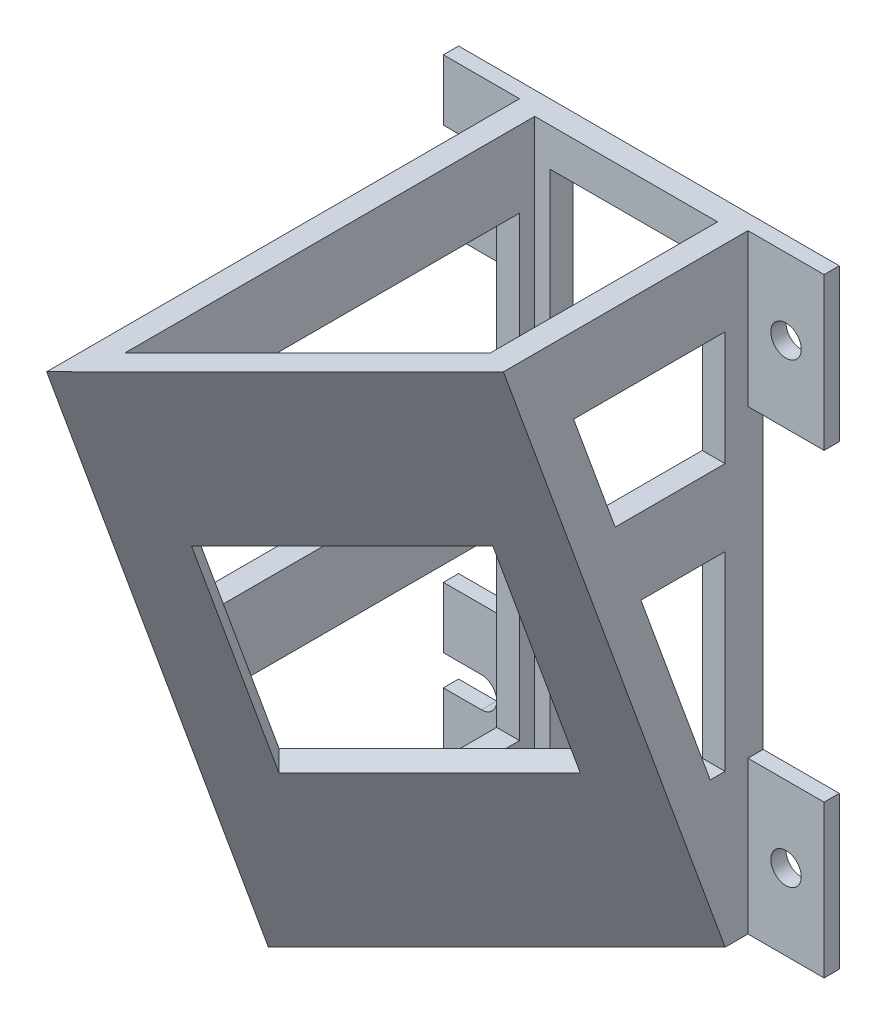
SolidWorks part; units mm, degrees
ref_plane "前视基准面" through (0, 0, 0) normal (0, 0, 1) x (1, 0, 0)
ref_plane "上视基准面" through (0, 0, 0) normal (0, 1, 0) x (1, 0, 0)
ref_plane "右视基准面" through (0, 0, 0) normal (1, 0, 0) x (0, 0, -1)
sketch "草图1" plane through (0, 0, 0) normal (0, 0, 1) x (1, 0, 0)
  line L1 (25, 40) -> (-25, 40)
  line L2 (25, 40) -> (25, -40)
  line L3 (25, -40) -> (-25, -40)
  line L4 (-25, 40) -> (-25, -40)
  line L5 (25, 40) -> (-25, -40) construction
  line L6 (25, -40) -> (-25, 40) construction
  point P0 (0, 0)
  dimension "D1" = 80
  dimension "D2" = 50
extrude "凸台-拉伸1" add sketch "草图1" along normal blind 80
sketch "草图4" plane through (0, 0, 80) normal (0, 0, 1) x (1, 0, 0)
  line L1 (-25, 40) -> (25, 40)
  line L2 (-25, 40) -> (-25, -120)
  line L3 (-25, -120) -> (25, -120)
  line L4 (25, 40) -> (25, -120)
  line L5 (-25, 40) -> (25, -120) construction
  line L6 (-25, -120) -> (25, 40) construction
  point P4 (0, -40)
  dimension "D1" = 160
revolve "切除-旋转2" cut sketch "草图4" angle 20 about L1
sketch "草图5" plane through (0, -21.0324, 57.786) normal (0, -0.342, 0.9397) x (1, 0, 0)
  line L1 (-25, 64.9493) -> (75, 64.9493)
  line L2 (-25, 64.9493) -> (-25, -95.0507)
  line L3 (-25, -95.0507) -> (75, -95.0507)
  line L4 (75, 64.9493) -> (75, -95.0507)
  line L5 (-25, 64.9493) -> (75, -95.0507) construction
  line L6 (-25, -95.0507) -> (75, 64.9493) construction
  point P4 (25, -15.0507)
  dimension "D1" = 100
  dimension "D2" = 160
revolve "切除-旋转4" cut sketch "草图5" angle 43.2 about L2
sketch "草图6" plane through (0, 0, 0) normal (0, 0, -1) x (-1, 0, 0)
  line L0 (25, -40) -> (-25, -40) construction
  line L1 (-15, -40) -> (-25, -40)
  line L2 (-15, -40) -> (-15, 40)
  line L3 (-15, 40) -> (-25, 40)
  line L4 (-25, -40) -> (-25, 40)
  line L5 (-15, -40) -> (-25, 40) construction
  line L6 (-15, 40) -> (-25, -40) construction
  line L7 (-25, 40) -> (25, 40) construction
  line L8 (-25, -40) -> (-25, 40) construction
  line L10 (25, -40) -> (14.9998, -40)
  line L11 (25, -40) -> (25, 40)
  line L12 (25, 40) -> (14.9998, 40)
  line L13 (14.9998, -40) -> (14.9998, 40)
  line L14 (25, -40) -> (14.9998, 40) construction
  line L15 (25, 40) -> (14.9998, -40) construction
  point P4 (-20, 0)
  point P15 (19.9999, 0)
  dimension "D1" = 10
  dimension "D2" = 0
extrude "切除-拉伸1" cut sketch "草图6" against normal blind 80
sketch "草图7" plane through (15, 0, 0) normal (1, 0, 0) x (0, 0, -1)
  line L0 (-40.0268, 40) -> (0, 40) construction
  line L1 (0, -40) -> (-5.91, -40)
  line L2 (0, -40) -> (0, 40)
  line L3 (0, 40) -> (-5.91, 40)
  line L4 (-5.91, -40) -> (-5.91, 40)
  line L5 (0, -40) -> (-5.91, 40) construction
  line L6 (0, 40) -> (-5.91, -40) construction
  point P4 (-2.955, 0)
  dimension "D1" = 5.91
extrude "切除-拉伸2" cut sketch "草图7" against normal blind 50
shell "抽壳2" thickness 3
sketch "草图8" plane through (0, 0, 5.91) normal (0, 0, -1) x (-1, 0, 0)
  line L0 (14.9998, -40) -> (-15, -40) construction
  line L1 (9.9998, -35) -> (-10, -35)
  line L2 (9.9998, -35) -> (9.9998, 35)
  line L3 (9.9998, 35) -> (-10, 35)
  line L4 (-10, -35) -> (-10, 35)
  line L5 (9.9998, -35) -> (-10, 35) construction
  line L6 (9.9998, 35) -> (-10, -35) construction
  line L7 (14.9998, 40) -> (-15, 40) construction
  line L8 (14.9998, 40) -> (14.9998, -40) construction
  line L9 (-15, 40) -> (-15, -40) construction
  point P4 (-0.0001, 0)
  dimension "D1" = 5
  dimension "D2" = 5
  dimension "D3" = 5
  dimension "D4" = 5
extrude "切除-拉伸3" cut sketch "草图8" against normal blind 3
sketch "草图9" plane through (0, 40, 0) normal (0, 1, 0) x (1, 0, 0)
  line L0 (12, -8.91) -> (-11.9998, -8.91)
  line L1 (-11.9998, -8.91) -> (-11.9998, -62.7673)
  line L2 (-11.9998, -62.7673) -> (12, -38.7836)
  line L3 (12, -38.7836) -> (12, -8.91)
  line L4 (-14.9998, -5.91) -> (15, -5.91) construction
  line L5 (15, -40.0268) -> (15, -5.91) construction
  line L6 (-14.9998, -70.0065) -> (-14.9998, -5.91) construction
  line L7 (15, -40.0268) -> (-14.9998, -70.0065) construction
  point P12 (0.0001, -50.7754)
  dimension "D1" = 3
  dimension "D2" = 3
  dimension "D3" = 3
  dimension "D4" = 0
  dimension "D5" = 3
extrude "切除-拉伸4" cut sketch "草图9" against normal blind 3
sketch "草图10" plane through (0, -40, 0) normal (0, -1, 0) x (1, 0, 0)
  line L0 (12.7565, 8.91) -> (-11.9998, 8.91)
  line L1 (-11.9998, 8.91) -> (-11.9998, 33.6496)
  line L2 (-11.9998, 33.6496) -> (12.7565, 8.91)
  line L3 (-14.9998, 5.91) -> (15, 5.91) construction
  line L4 (-14.9998, 40.8888) -> (-14.9998, 5.91) construction
  line L5 (-14.9998, 40.8888) -> (15, 10.9092) construction
  point P9 (0.3784, 21.2798)
  dimension "D1" = 3
  dimension "D2" = 3
  dimension "D3" = 0
  dimension "D4" = 3
extrude "切除-拉伸5" cut sketch "草图10" against normal blind 3
sketch "草图11" plane through (-14.9998, 0, 0) normal (-1, 0, 0) x (0, 0, 1)
  line L0 (10.91, -30) -> (10.91, -5)
  line L1 (10.91, -5) -> (48.3069, -5)
  line L2 (48.3069, -5) -> (39.2077, -30)
  line L3 (39.2077, -30) -> (10.91, -30)
  line L4 (10.91, 5) -> (10.91, 30)
  line L5 (10.91, 30) -> (61.0459, 30)
  line L6 (61.0459, 30) -> (51.9466, 5)
  line L7 (51.9466, 5) -> (10.91, 5)
  line L8 (40.8888, -40) -> (5.91, -40) construction
  line L9 (5.91, 40) -> (5.91, -40) construction
  line L10 (70.0065, 40) -> (5.91, 40) construction
  line L11 (40.8888, -40) -> (70.0065, 40) construction
  point P16 (43.7573, -17.5)
  point P17 (56.4962, 17.5)
  dimension "D1" = 10
  dimension "D2" = 5
  dimension "D3" = 10
  dimension "D4" = 360
  dimension "D5" = 0
  dimension "D6" = 5
  dimension "D7" = 5
  dimension "D8" = 10
  dimension "D9" = 25
  dimension "D10" = 25
extrude "切除-拉伸6" cut sketch "草图11" against normal blind 3
sketch "草图15" plane through (15, 0, 0) normal (1, 0, 0) x (0, 0, -1)
  line L0 (-30.8075, 30) -> (-10.91, 30)
  line L1 (-10.91, 30) -> (-10.91, 15)
  line L2 (-10.91, 15) -> (-25.348, 15)
  line L3 (-25.348, 15) -> (-30.8075, 30)
  line L4 (-40.0268, 40) -> (-5.91, 40) construction
  line L5 (-5.91, 40) -> (-5.91, -40) construction
  line L6 (-40.0268, 40) -> (-10.9092, -40) construction
  line L8 (-10.91, 5) -> (-10.91, -20)
  line L9 (-10.91, -20) -> (-12.8677, -20)
  line L10 (-12.8677, -20) -> (-21.967, 5)
  line L11 (-21.967, 5) -> (-10.91, 5)
  line L12 (-10.9092, -40) -> (-5.91, -40) construction
  point P16 (-17.4173, -7.5)
  dimension "D1" = 10
  dimension "D2" = 5
  dimension "D3" = 0
  dimension "D4" = 5
  dimension "D5" = 10
  dimension "D6" = 20
  dimension "D7" = 0
  dimension "D8" = 5
  dimension "D9" = 25
extrude "切除-拉伸7" cut sketch "草图15" against normal blind 3
sketch "草图17" plane through (18.9715, -6.9097, 18.9842) normal (0.6845, -0.2493, 0.685) x (0.729, 0.2341, -0.6433)
  line L0 (-39.6018, 0.4173) -> (-12.4481, -6.3482)
  line L1 (-12.4481, -6.3482) -> (-12.4481, 27.2575)
  line L2 (-12.4481, 27.2575) -> (-39.6018, 34.0229)
  line L3 (-39.6018, 34.0229) -> (-39.6018, 0.4173)
  line L4 (-5.4481, 51.2777) -> (-46.6018, 61.5313) construction
  line L5 (-5.4481, 51.2777) -> (-5.4481, -33.8565) construction
  line L6 (-46.6018, -23.6029) -> (-46.6018, 61.5313) construction
  line L7 (-46.6018, -23.6029) -> (-5.4481, -33.8565) construction
  point P12 (-12.4481, 10.4547)
  point P13 (-26.025, 30.6402)
  point P14 (-39.6018, 17.2201)
  point P15 (-26.025, -2.9654)
  point P17 (-21.9806, 24.8721)
  dimension "D1" = 0
  dimension "D2" = 0
  dimension "D3" = 0
  dimension "D4" = 0
  dimension "D5" = 7
  dimension "D6" = 25
  dimension "D7" = 7
  dimension "D8" = 25
extrude "切除-拉伸9" cut sketch "草图17" against normal blind 3
sketch "草图18" plane through (15, 0, 0) normal (1, 0, 0) x (0, 0, -1)
  line L1 (-5.91, -40) -> (-7.91, -40)
  line L2 (-5.91, -40) -> (-5.91, -20)
  line L3 (-5.91, -20) -> (-7.91, -20)
  line L4 (-7.91, -40) -> (-7.91, -20)
  line L5 (-5.91, -40) -> (-7.91, -20) construction
  line L6 (-5.91, -20) -> (-7.91, -40) construction
  line L7 (-5.91, 40) -> (-7.91, 40)
  line L8 (-5.91, 40) -> (-5.91, 20)
  line L9 (-5.91, 20) -> (-7.91, 20)
  line L10 (-7.91, 40) -> (-7.91, 20)
  line L11 (-5.91, 40) -> (-7.91, 20) construction
  line L12 (-5.91, 20) -> (-7.91, 40) construction
  point P4 (-6.91, -30)
  point P10 (-6.91, 30)
  dimension "D1" = 20
  dimension "D2" = 20
  dimension "D3" = 2
  dimension "D4" = 2
extrude "凸台-拉伸2" add sketch "草图18" along normal blind 10
sketch "草图19" plane through (-14.9998, 0, 0) normal (-1, 0, 0) x (0, 0, 1)
  line L1 (5.91, 40) -> (7.91, 40)
  line L2 (5.91, 40) -> (5.91, 20)
  line L3 (5.91, 20) -> (7.91, 20)
  line L4 (7.91, 40) -> (7.91, 20)
  line L5 (5.91, 40) -> (7.91, 20) construction
  line L6 (5.91, 20) -> (7.91, 40) construction
  line L7 (5.91, -40) -> (7.91, -40)
  line L8 (5.91, -40) -> (5.91, -20)
  line L9 (5.91, -20) -> (7.91, -20)
  line L10 (7.91, -40) -> (7.91, -20)
  line L11 (5.91, -40) -> (7.91, -20) construction
  line L12 (5.91, -20) -> (7.91, -40) construction
  point P4 (6.91, 30)
  point P10 (6.91, -30)
  dimension "D1" = 2
  dimension "D2" = 20
  dimension "D3" = 2
  dimension "D4" = 20
extrude "凸台-拉伸3" add sketch "草图19" along normal blind 10
sketch "草图20" plane through (0, 0, 5.91) normal (0, 0, -1) x (-1, 0, 0)
  line L0 (24.9998, 40) -> (24.9998, 30)
  line L1 (24.9998, 40) -> (24.9998, 20) construction
  line L2 (24.9998, 30) -> (19.9998, 30)
  line L3 (24.9998, -40) -> (24.9998, -30)
  line L4 (24.9998, -20) -> (24.9998, -40) construction
  line L5 (24.9998, -30) -> (19.9998, -30)
  line L6 (-25, 40) -> (-25, 30)
  line L7 (-25, 20) -> (-25, 40) construction
  line L8 (-25, 30) -> (-20, 30)
  line L9 (-25, -40) -> (-25, -30)
  line L10 (-25, -40) -> (-25, -20) construction
  line L11 (-25, -30) -> (-20, -30)
  line L12 (19.9998, 32) -> (24.9998, 32)
  line L13 (24.9998, 32) -> (24.9998, 28)
  line L14 (24.9998, 28) -> (19.9998, 28)
  line L15 (19.9998, -28) -> (24.9998, -28)
  line L16 (24.9998, -28) -> (24.9998, -32)
  line L17 (24.9998, -32) -> (19.9998, -32)
  circle A0 centre (19.9998, 30) radius 2
  circle A1 centre (19.9998, -30) radius 2
  circle A2 centre (-20, 30) radius 2
  circle A3 centre (-20, -30) radius 2
  dimension "D5" = 4
  dimension "D1" = 5
  dimension "D2" = 5
  dimension "D3" = 5
  dimension "D4" = 5
  dimension "D6" = 4
extrude "切除-拉伸10" cut sketch "草图20" against normal blind 2
